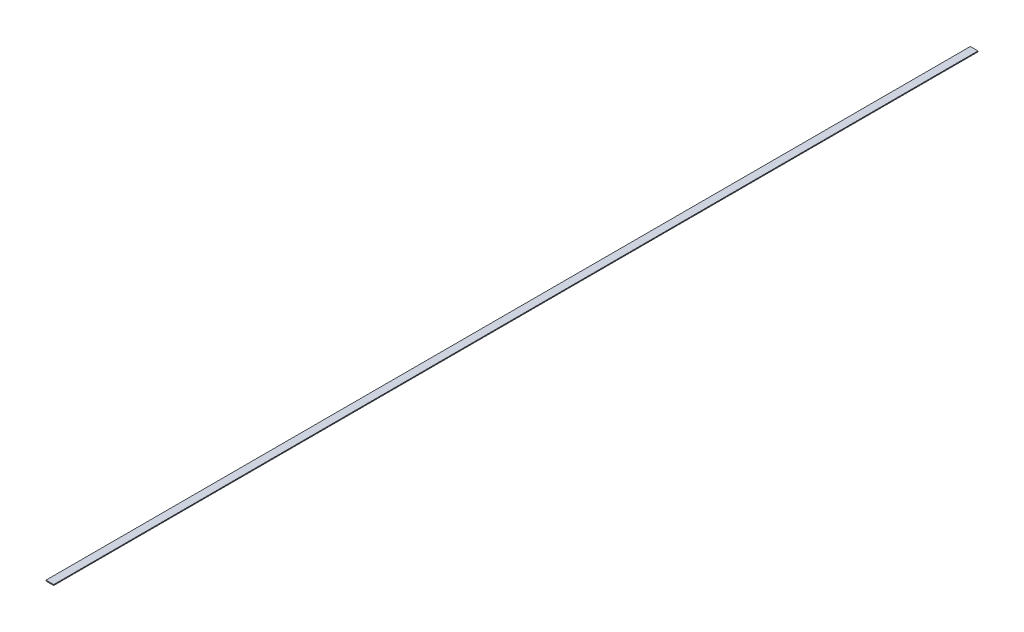
SolidWorks part; units mm, degrees
ref_plane "Front Plane" through (0, 0, 0) normal (0, 0, 1) x (1, 0, 0)
ref_plane "Top Plane" through (0, 0, 0) normal (0, 1, 0) x (1, 0, 0)
ref_plane "Right Plane" through (0, 0, 0) normal (1, 0, 0) x (0, 0, -1)
sketch "Sketch1" plane through (0, 0, 0) normal (0, 0, 1) x (1, 0, 0)
  line L0 (6505.0765, 4658.5445) -> (6505.0765, 4657.1475)
  line L1 (6517.7765, 4658.5445) -> (6517.7765, 4657.1475)
  line L2 (6517.7765, 4658.5445) -> (6505.0765, 4658.5445)
  line L3 (6517.7765, 4657.1475) -> (6505.0765, 4657.1475)
extrude "Boss-Extrude1" add sketch "Sketch1" along normal blind 1524
